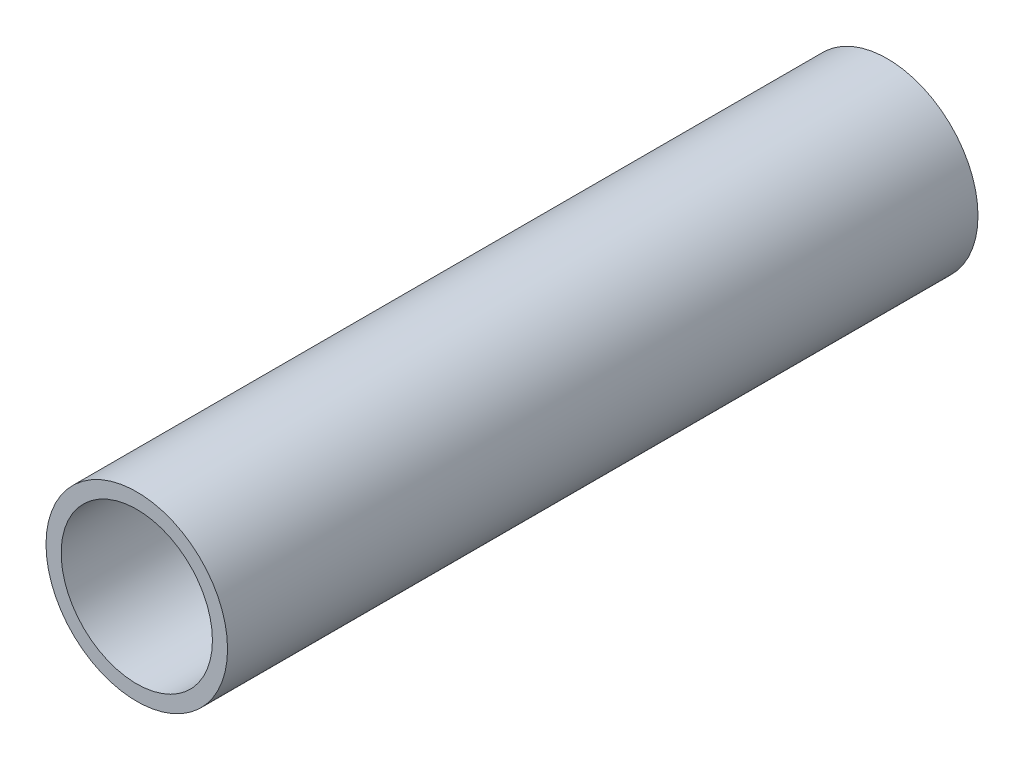
SolidWorks part; units mm, degrees
ref_plane "Front Plane" through (0, 0, 0) normal (0, 0, 1) x (1, 0, 0)
ref_plane "Top Plane" through (0, 0, 0) normal (0, 1, 0) x (1, 0, 0)
ref_plane "Right Plane" through (0, 0, 0) normal (1, 0, 0) x (0, 0, -1)
sketch "Sketch1" plane through (0, 0, 0) normal (0, 0, 1) x (1, 0, 0)
  circle A0 centre (0, 0) radius 15
  circle A1 centre (0, 0) radius 12.5
  dimension "D1" = 25
  dimension "D2" = 30
extrude "Boss-Extrude1" add sketch "Sketch1" along normal blind 124
